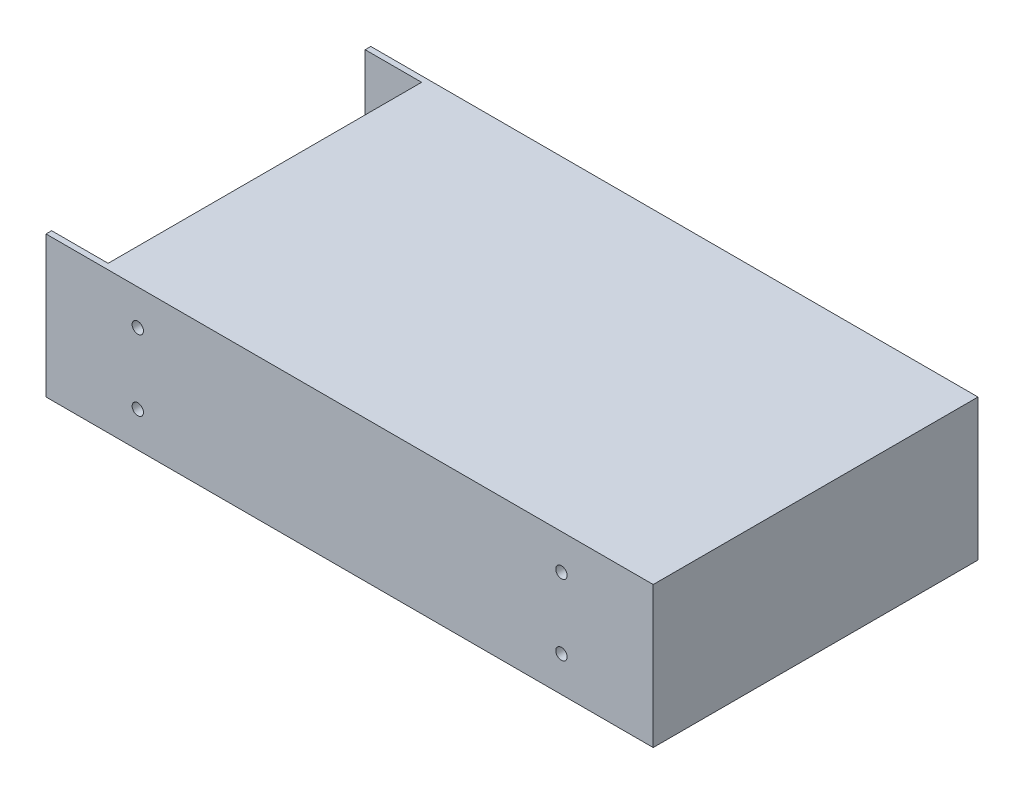
SolidWorks part; units mm, degrees
ref_plane "Front Plane" through (0, 0, 0) normal (0, 0, 1) x (1, 0, 0)
ref_plane "Top Plane" through (0, 0, 0) normal (0, 1, 0) x (1, 0, 0)
ref_plane "Right Plane" through (0, 0, 0) normal (1, 0, 0) x (0, 0, -1)
sketch "Sketch1" plane through (0, 0, 0) normal (0, 1, 0) x (1, 0, 0)
  line L1 (-107.5, 57.5) -> (107.5, 57.5)
  line L2 (-107.5, 57.5) -> (-107.5, -57.5)
  line L3 (-107.5, -57.5) -> (107.5, -57.5)
  line L4 (107.5, 57.5) -> (107.5, -57.5)
  line L5 (-107.5, 57.5) -> (107.5, -57.5) construction
  line L6 (-107.5, -57.5) -> (107.5, 57.5) construction
  point P0 (0, 0)
  dimension "D1" = 115
  dimension "D2" = 215
extrude "Boss-Extrude1" add sketch "Sketch1" along normal blind 50
sketch "Sketch2" plane through (0, 50, 0) normal (0, 1, 0) x (1, 0, 0)
  line L0 (-107.5, 57.5) -> (-107.5, -57.5) construction
  line L1 (-87.5, -55.5) -> (-107.5, -55.5)
  line L2 (-87.5, -55.5) -> (-87.5, 55.5)
  line L3 (-87.5, 55.5) -> (-107.5, 55.5)
  line L4 (-107.5, -55.5) -> (-107.5, 55.5)
  line L5 (-87.5, -55.5) -> (-107.5, 55.5) construction
  line L6 (-87.5, 55.5) -> (-107.5, -55.5) construction
  line L7 (107.5, 57.5) -> (-107.5, 57.5) construction
  point P0 (-97.5, 0)
  dimension "D1" = 20
  dimension "D2" = 2
extrude "Cut-Extrude1" cut sketch "Sketch2" against normal blind 30
sketch "Sketch3" plane through (0, 0, 0) normal (0, -1, 0) x (1, 0, 0)
  line L0 (107.5, -57.5) -> (-107.5, -57.5) construction
  line L1 (-107.5, -57.5) -> (-107.5, 57.5) construction
  circle A0 centre (-75, 25) radius 2
  circle A1 centre (75, 25) radius 2
  circle A2 centre (75, -25) radius 2
  circle A3 centre (-75, -25) radius 2
  dimension "D1" = 32.5
  dimension "D3" = 4
  dimension "D2" = 50
  dimension "D4" = 32.5
  dimension "D5" = 150
extrude "Cut-Extrude2" cut sketch "Sketch3" against normal blind 5
sketch "Sketch4" plane through (0, 0, 57.5) normal (0, 0, 1) x (1, 0, 0)
  line L0 (-107.5, 50) -> (-107.5, 0) construction
  line L1 (-75, 37.5) -> (75, 37.5) construction
  line L2 (-75, 37.5) -> (-75, 12.5) construction
  line L3 (-75, 12.5) -> (75, 12.5) construction
  line L4 (75, 37.5) -> (75, 12.5) construction
  line L5 (-75, 37.5) -> (75, 12.5) construction
  line L6 (-75, 12.5) -> (75, 37.5) construction
  circle A0 centre (-75, 12.5) radius 2
  circle A1 centre (-75, 37.5) radius 2
  circle A2 centre (75, 37.5) radius 2
  circle A3 centre (75, 12.5) radius 2
  point P0 (0, 25)
  point P11 (0, 0)
  point P12 (-107.5, 25)
  dimension "D1" = 150
  dimension "D4" = 4
  dimension "D2" = 25
  dimension "D3" = 32.5
extrude "Cut-Extrude3" cut sketch "Sketch4" against normal blind 3
